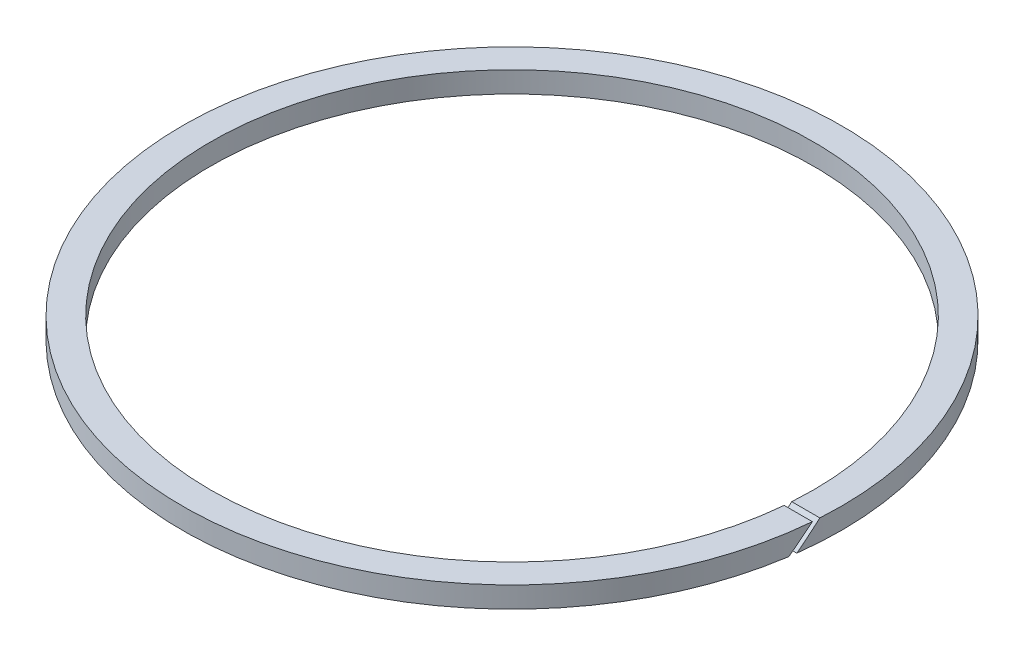
SolidWorks part; units mm, degrees
ref_plane "Front Plane" through (0, 0, 0) normal (0, 0, 1) x (1, 0, 0)
ref_plane "Top Plane" through (0, 0, 0) normal (0, 1, 0) x (1, 0, 0)
ref_plane "Right Plane" through (0, 0, 0) normal (1, 0, 0) x (0, 0, -1)
sketch "Sketch1" plane through (0, 0, 0) normal (0, 1, 0) x (1, 0, 0)
  circle A0 centre (0, 0) radius 47
  circle A1 centre (0, 0) radius 43
  dimension "D1" = 94
  dimension "D2" = 86
extrude "Boss-Extrude1" add sketch "Sketch1" along normal blind 3
sketch "Sketch2" plane through (0, 3, 0) normal (0, 1, 0) x (1, 0, 0)
  line L0 (-40.3287, 0) -> (47.8476, 0) construction
  line L1 (0, 36.7484) -> (0, -25.7983) construction
ref_plane "Plane1" through (47, 0, 0) normal (1, 0, 0) x (0, 0, -1)
sketch "Sketch3" plane through (47, 0, 0) normal (1, 0, 0) x (0, 0, -1)
  line L0 (-55.8528, 1.5) -> (65.5626, 1.5) construction
  line L1 (-4, 3) -> (-7, 0)
  line L2 (36.7484, 3) -> (-25.7983, 3) construction
  line L3 (-3, 3) -> (-6, 0)
  line L4 (-47, 0) -> (47, 0) construction
  line L5 (-4, 3) -> (-3, 3)
  line L6 (-7, 0) -> (-6, 0)
  dimension "D1" = 1.5
  dimension "D2" = 1
  dimension "D3" = 1
  dimension "D4" = 135
  dimension "D5" = 3
extrude "Cut-Extrude1" cut sketch "Sketch3" against normal blind 10
